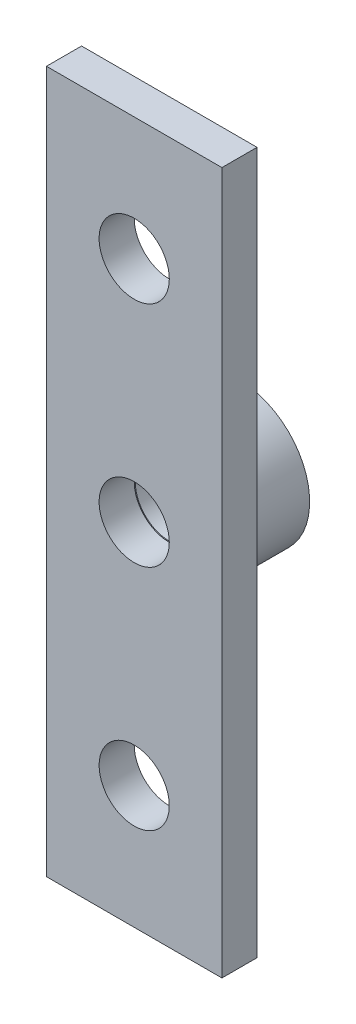
SolidWorks part; units mm, degrees
ref_plane "Ön Düzlem" through (0, 0, 0) normal (0, 0, 1) x (1, 0, 0)
ref_plane "Üst Düzlem" through (0, 0, 0) normal (0, 1, 0) x (1, 0, 0)
ref_plane "Sağ Düzlem" through (0, 0, 0) normal (1, 0, 0) x (0, 0, -1)
sketch "Çizim1" plane through (0, 0, 0) normal (0, 0, 1) x (1, 0, 0)
  line L0 (0, 20) -> (10, 20) construction
  line L1 (0, 0) -> (10, 0)
  line L2 (0, 0) -> (0, 40)
  line L3 (0, 40) -> (10, 40)
  line L4 (10, 0) -> (10, 40)
  circle A0 centre (5, 20) radius 2
  circle A1 centre (5, 33) radius 2
  circle A2 centre (5, 7) radius 2
  dimension "D3" = 4
  dimension "D4" = 4
  dimension "D5" = 7
  dimension "D1" = 40
  dimension "D2" = 10
extrude "Yükseklik-Ekstrüzyon1" add sketch "Çizim1" along normal blind 2
sketch "Çizim2" plane through (0, 0, 0) normal (0, 0, -1) x (-1, 0, 0)
  circle A0 centre (-5, 20) radius 4
  circle A1 centre (-5, 20) radius 1.9376
  dimension "D1" = 8
extrude "Yükseklik-Ekstrüzyon2" add sketch "Çizim2" along normal blind 4
